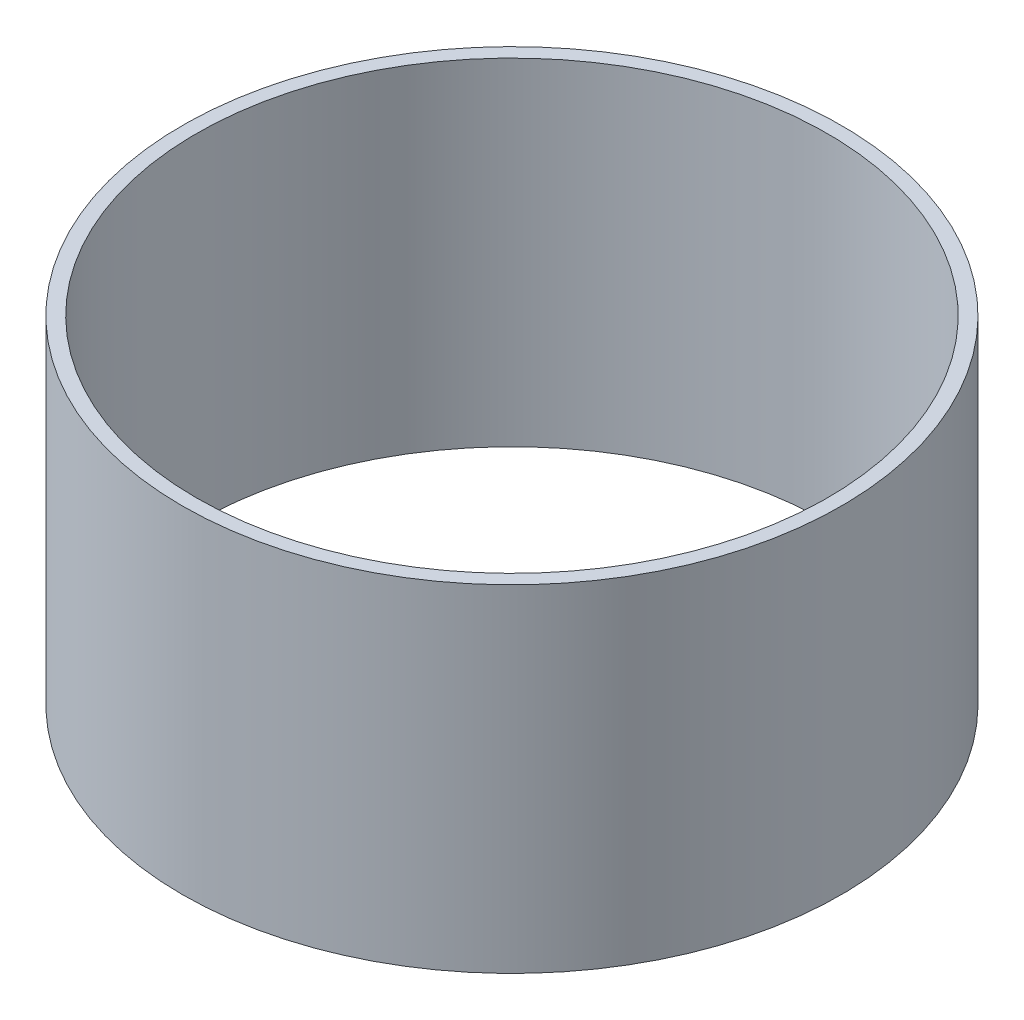
SolidWorks part; units mm, degrees
ref_plane "Front Plane" through (0, 0, 0) normal (0, 0, 1) x (1, 0, 0)
ref_plane "Top Plane" through (0, 0, 0) normal (0, 1, 0) x (1, 0, 0)
ref_plane "Right Plane" through (0, 0, 0) normal (1, 0, 0) x (0, 0, -1)
sketch "Sketch1" plane through (0, 0, 0) normal (0, 1, 0) x (1, 0, 0)
  circle A0 centre (0, 0) radius 285.75
  circle A1 centre (0, 0) radius 298.45
  dimension "D1" = 571.5
  dimension "D2" = 596.9
extrude "Boss-Extrude1" add sketch "Sketch1" against normal blind 304.8
